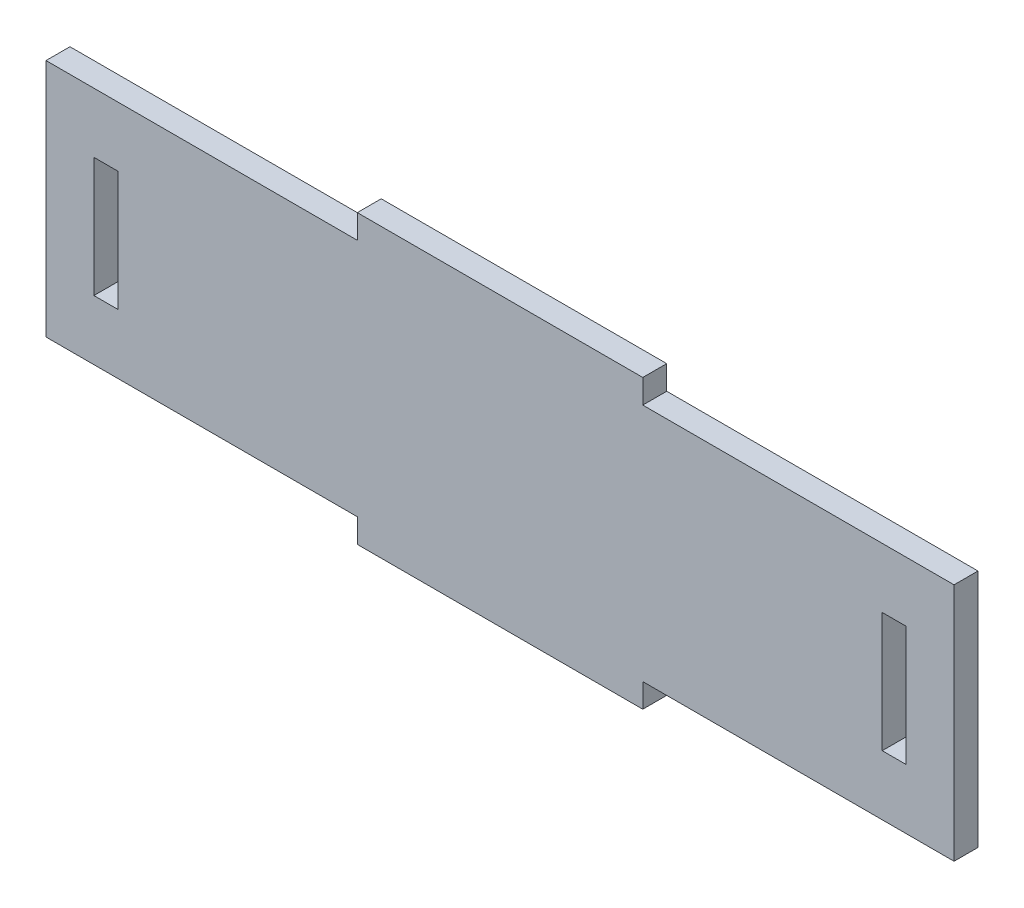
SolidWorks part; units mm, degrees
ref_plane "Front Plane" through (0, 0, 0) normal (0, 0, 1) x (1, 0, 0)
ref_plane "Top Plane" through (0, 0, 0) normal (0, 1, 0) x (1, 0, 0)
ref_plane "Right Plane" through (0, 0, 0) normal (1, 0, 0) x (0, 0, -1)
sketch "Sketch1" plane through (0, 0, 0) normal (0, 0, 1) x (1, 0, 0)
  line L0 (0, 0) -> (24, 0)
  line L2 (0, 0) -> (0, 20) construction
  line L4 (71.848, 0) -> (71.848, 20) construction
  line L5 (24, 0) -> (24, -2)
  line L6 (24, -2) -> (47.848, -2)
  line L7 (47.848, -2) -> (47.848, 0)
  line L8 (47.848, 0) -> (71.848, 0)
  line L9 (0, 20) -> (24, 20)
  line L10 (24, 20) -> (24, 22)
  line L11 (24, 22) -> (47.848, 22)
  line L12 (47.848, 22) -> (47.848, 20)
  line L13 (47.848, 20) -> (71.848, 20)
  line L14 (0, 20) -> (-2, 20)
  line L19 (2, 15) -> (4, 15)
  line L20 (2, 15) -> (2, 5)
  line L21 (2, 5) -> (4, 5)
  line L22 (4, 15) -> (4, 5)
  line L23 (67.848, 15) -> (69.848, 15)
  line L24 (67.848, 15) -> (67.848, 5)
  line L25 (67.848, 5) -> (69.848, 5)
  line L26 (69.848, 15) -> (69.848, 5)
  line L27 (-2, 20) -> (-2, 0)
  line L28 (-2, 0) -> (0, 0)
  line L29 (71.848, 20) -> (73.848, 20)
  line L30 (73.848, 20) -> (73.848, 0)
  line L31 (73.848, 0) -> (71.848, 0)
  dimension "D1" = 20
  dimension "D2" = 5
  dimension "D3" = 5
  dimension "D6" = 2
  dimension "D7" = 5
  dimension "D8" = 5
  dimension "D9" = 2
extrude "Boss-Extrude1" add sketch "Sketch1" along normal blind 2
